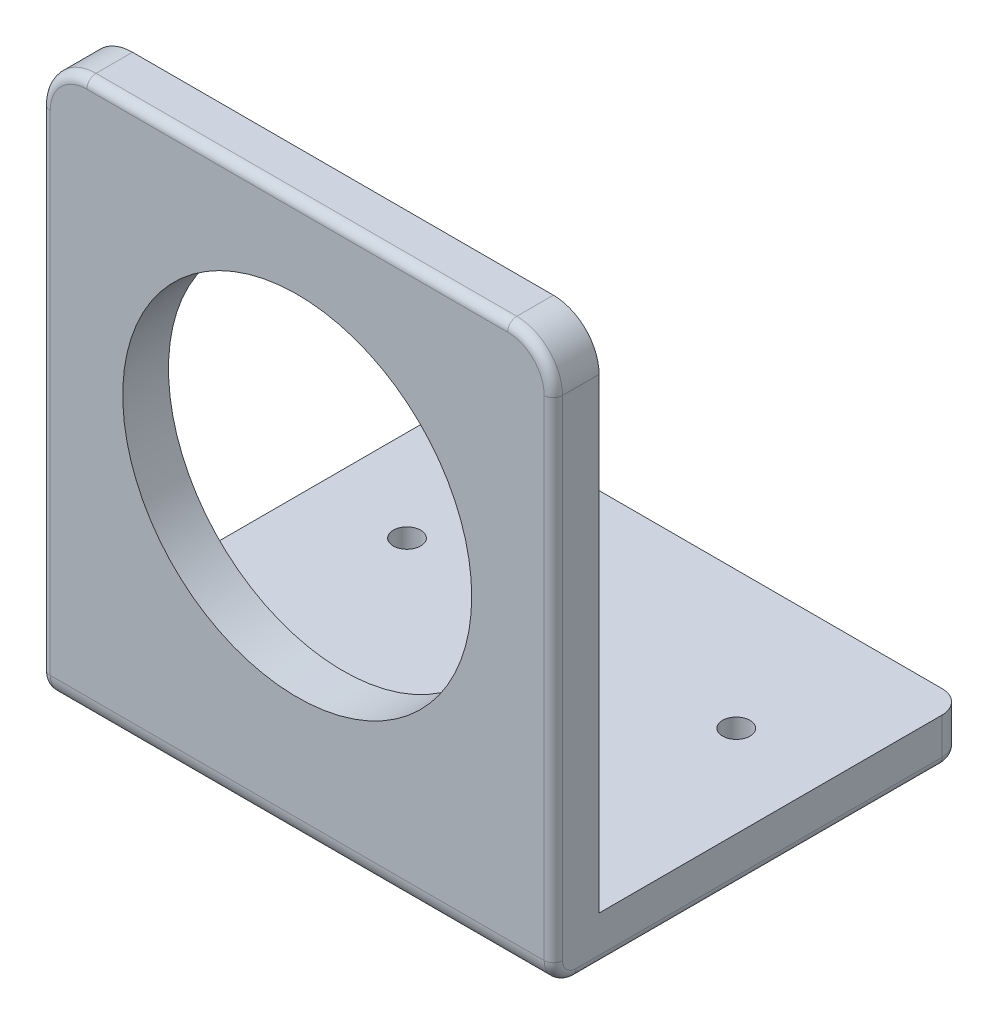
SolidWorks part; units mm, degrees
ref_plane "Plan de face" through (0, 0, 0) normal (0, 0, 1) x (1, 0, 0)
ref_plane "Plan de dessus" through (0, 0, 0) normal (0, 1, 0) x (1, 0, 0)
ref_plane "Plan de droite" through (0, 0, 0) normal (1, 0, 0) x (0, 0, -1)
sketch "Esquisse1" plane through (0, 0, 0) normal (0, 0, 1) x (1, 0, 0)
  line L1 (-23, 28) -> (23, 28)
  line L2 (-28, 23) -> (-28, -28)
  line L3 (-28, -28) -> (28, -28)
  line L4 (28, 23) -> (28, -28)
  line L5 (-28, 28) -> (28, -28) construction
  line L6 (-28, -28) -> (28, 28) construction
  circle A0 centre (0, 0) radius 19.075
  arc A1 (23, 28) -> (28, 23) centre (23, 23) cw
  arc A2 (-23, 28) -> (-28, 23) centre (-23, 23) ccw
  point P0 (0, 0)
  dimension "D3" = 38.15
  dimension "D4" = 5
  dimension "D1" = 56
  dimension "D2" = 56
extrude "Boss.-Extru.2" add sketch "Esquisse1" along normal blind 5
sketch "Esquisse2" plane through (0, -28, 0) normal (0, -1, 0) x (1, 0, 0)
  line L4 (-28, 0) -> (28, 0)
  line L5 (28, 0) -> (28, 5)
  line L6 (28, 5) -> (-28, 5)
  line L7 (-28, 5) -> (-28, 0)
  line L8 (-28, 0) -> (28, 0)
  line L9 (28, 0) -> (28, 5)
  line L10 (28, 5) -> (-28, 5)
  line L11 (-28, 5) -> (-28, 0)
  dimension "D1" = 0
extrude "Boss.-Extru.3" add sketch "Esquisse2" along normal blind 5
sketch "Esquisse3" plane through (0, 0, 0) normal (0, 0, -1) x (-1, 0, 0)
  line L0 (-28, -28) -> (28, -28)
  line L4 (-28, 23) -> (-28, -33)
  line L5 (-28, -33) -> (28, -33)
  line L6 (28, -33) -> (28, 23)
  line L7 (23, 28) -> (-23, 28)
  line L8 (-28, -28) -> (-28, -33)
  line L9 (-28, -33) -> (28, -33)
  line L10 (28, -33) -> (28, -28)
  arc A2 (28, 23) -> (23, 28) centre (23, 23) ccw
  arc A3 (-23, 28) -> (-28, 23) centre (-23, 23) ccw
  dimension "D2" = 5
  dimension "D1" = 0
extrude "Boss.-Extru.4" add sketch "Esquisse3" along normal blind 50
fillet "Congé1" radius 2.5 1 edges at (0, -33, 5)
sketch "Esquisse5" plane through (0, -28, 0) normal (0, 1, 0) x (1, 0, 0)
  line L0 (-28, 25) -> (28, 25) construction
  line L1 (-28, 50) -> (-28, 0) construction
  line L2 (28, 50) -> (28, 0) construction
  line L3 (0, 0) -> (0, 50) construction
  line L4 (-28, 50) -> (28, 50) construction
  circle A0 centre (-18, 25) radius 1.5
  circle A1 centre (18, 25) radius 1.5
  dimension "D1" = 3
  dimension "D2" = 10
extrude "Enlèv. mat.-Extru.2" cut sketch "Esquisse5" against normal blind 5
sketch "Esquisse6" plane through (0, 0, -50) normal (0, 0, -1) x (-1, 0, 0)
  line L4 (-28, -33) -> (28, -33)
  line L5 (28, -33) -> (28, -28)
  line L6 (28, -28) -> (-28, -28)
  line L7 (-28, -28) -> (-28, -33)
  line L8 (-28, -33) -> (28, -33)
  line L9 (28, -33) -> (28, -28)
  line L10 (28, -28) -> (-28, -28)
  line L11 (-28, -28) -> (-28, -33)
  dimension "D1" = 0
extrude "Enlèv. mat.-Extru.3" cut sketch "Esquisse6" against normal blind 10
fillet "Congé2" radius 2.5 2 edges at (-28, -30.5, -40) (28, -30.5, -40)
fillet "Congé3" radius 1 12 edges at (-26.5355, 26.5355, 5) (0, 28, 5) (26.5355, 26.5355, 5) (28, -3.75, 5) (28, -32.2678, 4.2678) (28, -33, -17.5) (-28, -33, -17.5) (-28, -32.2678, 4.2678) (-28, -3.75, 5) (27.2678, -33, -39.2678) (0, -33, -40) (-27.2678, -33, -39.2678)
